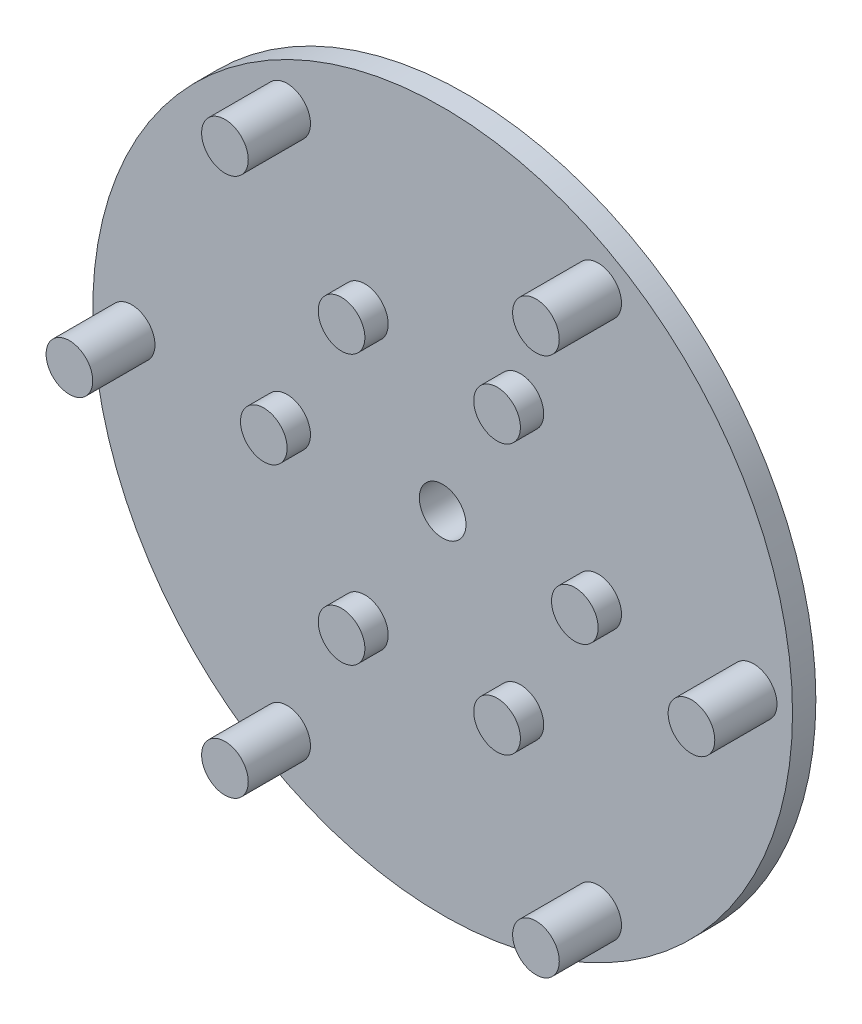
SolidWorks part; units mm, degrees
ref_plane "前视基准面" through (0, 0, 0) normal (0, 0, 1) x (1, 0, 0)
ref_plane "上视基准面" through (0, 0, 0) normal (0, 1, 0) x (1, 0, 0)
ref_plane "右视基准面" through (0, 0, 0) normal (1, 0, 0) x (0, 0, -1)
other "Configuration Table"
sketch "草图1" plane through (0, 0, 0) normal (0, 0, 1) x (1, 0, 0)
  circle A0 centre (0, 0) radius 45
  point P0 (0, 0)
  point P19 (0, 0)
  dimension "D1" = 90
extrude "凸台-拉伸1" add sketch "草图1" against normal blind 3 contours A0
sketch "草图2" plane through (0, 0, 0) normal (0, 0, 1) x (1, 0, 0)
  line L0 (0, 0) -> (-40, 0) construction
  circle A0 centre (0, 0) radius 3
  circle A1 centre (-40, 0) radius 3
  circle A2 centre (-20, 34.641) radius 3
  circle A3 centre (20, 34.641) radius 3
  circle A4 centre (40, 0) radius 3
  circle A5 centre (20, -34.641) radius 3
  circle A6 centre (-20, -34.641) radius 3
  point P17 (0, 0)
  dimension "D1" = 6
  dimension "D2" = 40
  dimension "D3" = 6
extrude "凸台-拉伸2" add sketch "草图2" along normal blind 8
sketch "草图3" plane through (0, 0, 0) normal (0, 0, 1) x (1, 0, 0)
  circle A0 centre (0, 0) radius 3
sketch "草图4" plane through (0, 0, 0) normal (0, 0, 1) x (1, 0, 0)
  line L0 (-20, 34.641) -> (0, 0) construction
  circle A0 centre (-10, 17.3205) radius 3
  circle A1 centre (10, 17.3205) radius 3
  circle A2 centre (20, 0) radius 3
  circle A3 centre (10, -17.3205) radius 3
  circle A4 centre (-10, -17.3205) radius 3
  circle A5 centre (-20, 0) radius 3
  point P18 (0, 0)
  dimension "D1" = 6
  dimension "D2" = 6
extrude "凸台-拉伸4" add sketch "草图4" along normal blind 3
extrude "切除-拉伸1" cut sketch "草图3" against normal up to next
sketch "草图5" plane through (0, 0, -3) normal (0, 0, -1) x (-1, 0, 0)
  circle A0 centre (0, 0) radius 6
  dimension "D1" = 12
extrude "拉伸-薄壁1" add sketch "草图5" along normal blind 6 thin thin type one direction reverse wall 3
